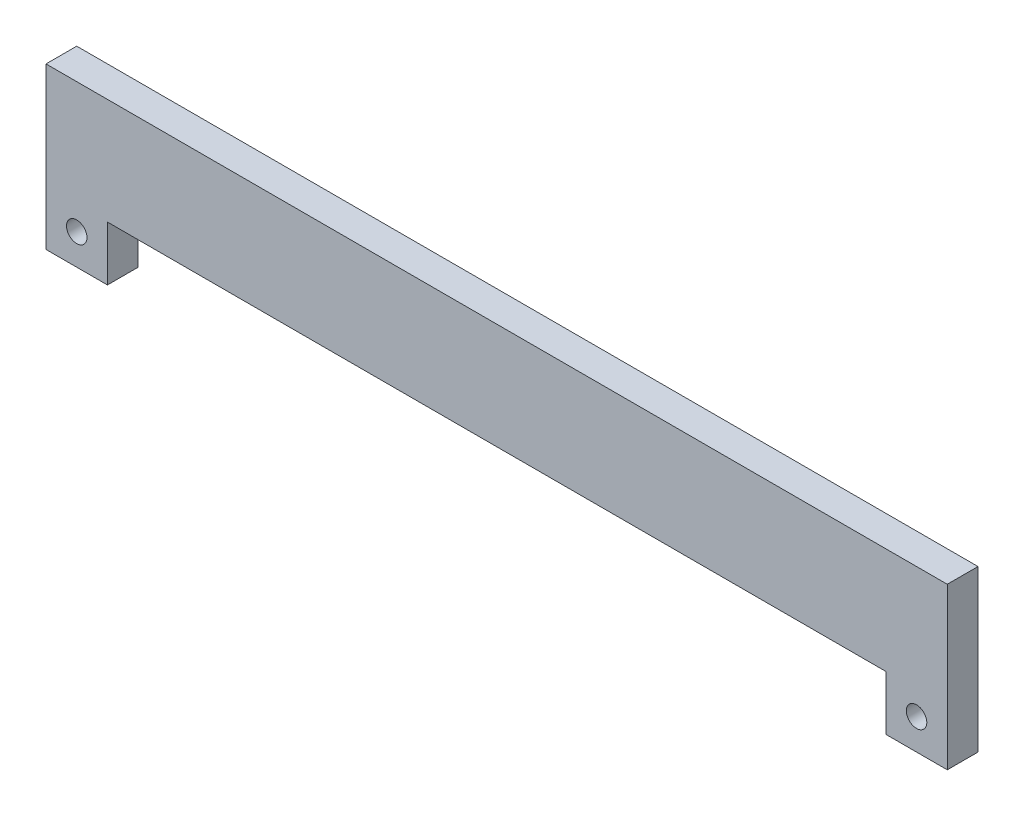
SolidWorks part; units mm, degrees
ref_plane "Front Plane" through (0, 0, 0) normal (0, 0, 1) x (1, 0, 0)
ref_plane "Top Plane" through (0, 0, 0) normal (0, 1, 0) x (1, 0, 0)
ref_plane "Right Plane" through (0, 0, 0) normal (1, 0, 0) x (0, 0, -1)
sketch "Sketch1" plane through (0, 0, 0) normal (0, 0, 1) x (1, 0, 0)
  line L0 (0, 87.6415) -> (0, -136.5505) construction
  line L1 (-241.3, -25.755) -> (241.3, -25.755)
  line L2 (241.3, -25.755) -> (241.3, -59.55)
  line L3 (241.3, -59.55) -> (279.4, -59.55)
  line L4 (279.4, -59.55) -> (279.4, 40.1)
  line L5 (279.4, 40.1) -> (-279.4, 40.1)
  line L6 (-279.4, -59.55) -> (-279.4, 40.1)
  line L7 (-241.3, -59.55) -> (-279.4, -59.55)
  line L8 (-241.3, -25.755) -> (-241.3, -59.55)
  line L10 (-233.6851, -33) -> (-233.6851, -48) construction
  line L11 (-64.4558, -33) -> (118.8308, -33) construction
  line L12 (118.8308, -48) -> (-64.4558, -48) construction
  line L13 (-233.6851, -40.5) -> (325.0672, -40.5) construction
  circle A0 centre (260.35, -40.5) radius 6.35
  circle A1 centre (52.9054, -17.5) radius 2 construction
  circle A2 centre (52.9054, -17.5) radius 2 construction
  circle A3 centre (-260.35, -40.5) radius 6.35
  point P10 (0, 40.1)
  point P13 (0, -25.755)
  dimension "D4" = 12.7
  dimension "D7" = 8.255
  dimension "D1" = 99.65
  dimension "D2" = 558.8
  dimension "D3" = 482.6
  dimension "D5" = 260.35
  dimension "D6" = 19.05
extrude "Boss-Extrude1" add sketch "Sketch1" along normal blind 19.05 contours L8 L1 L2 L3 L4 L5 L6 L7 A0 A3
